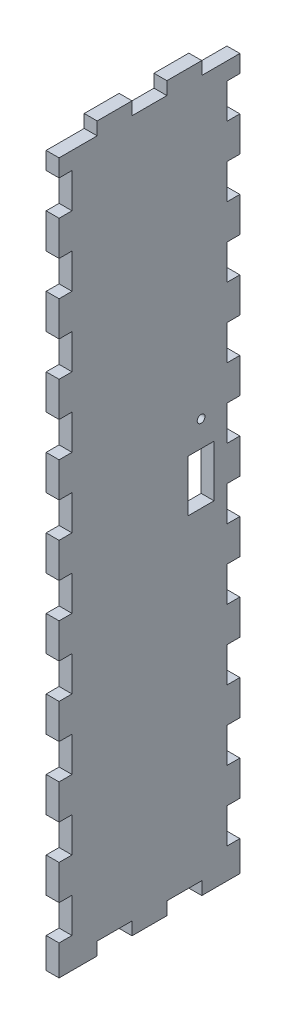
SolidWorks part; units mm, degrees
ref_plane "Front Plane" through (0, 0, 0) normal (0, 0, 1) x (1, 0, 0)
ref_plane "Top Plane" through (0, 0, 0) normal (0, 1, 0) x (1, 0, 0)
ref_plane "Right Plane" through (0, 0, 0) normal (1, 0, 0) x (0, 0, -1)
sketch "Sketch1" plane through (0, 0, 0) normal (1, 0, 0) x (0, 0, -1)
  line L0 (6.35, 355.6) -> (6.35, 349.25) construction
  line L1 (0, 0) -> (88.9, 0) construction
  line L2 (0, 0) -> (0, 6.35) construction
  line L3 (6.35, 355.6) -> (76.2, 355.6) construction
  line L4 (88.9, 0) -> (88.9, 6.35) construction
  line L5 (0, 6.35) -> (88.9, 6.35) construction
  line L6 (6.35, 349.25) -> (88.9, 349.25) construction
  line L7 (82.55, 355.6) -> (82.55, 338.1375) construction
  line L8 (0, 6.35) -> (0, 0)
  line L9 (0, 0) -> (6.35, 0)
  line L10 (6.35, 0) -> (18.7325, 0)
  line L11 (18.7325, 0) -> (18.7325, 6.35)
  line L12 (18.7325, 6.35) -> (35.8775, 6.35)
  line L13 (35.8775, 6.35) -> (35.8775, 0)
  line L14 (35.8775, 0) -> (53.0225, 0)
  line L15 (53.0225, 0) -> (53.0225, 6.35)
  line L16 (53.0225, 6.35) -> (70.1675, 6.35)
  line L17 (70.1675, 6.35) -> (70.1675, 0)
  line L18 (70.1675, 0) -> (82.55, 0)
  line L19 (82.55, 0) -> (88.9, 0)
  line L20 (88.9, 0) -> (88.9, 6.35)
  line L21 (6.35, 12.3825) -> (6.35, 0) construction
  line L22 (0, 0) -> (0, 349.25) construction
  line L23 (0, 6.35) -> (0, 14.9225)
  line L24 (0, 49.2125) -> (6.35, 49.2125)
  line L25 (6.35, 49.2125) -> (6.35, 66.3575)
  line L26 (6.35, 66.3575) -> (0, 66.3575)
  line L27 (0, 66.3575) -> (0, 83.5025)
  line L28 (0, 83.5025) -> (6.35, 83.5025)
  line L29 (6.35, 83.5025) -> (6.35, 100.6475)
  line L30 (6.35, 100.6475) -> (0, 100.6475)
  line L31 (0, 100.6475) -> (0, 117.7925)
  line L32 (0, 117.7925) -> (6.35, 117.7925)
  line L33 (6.35, 117.7925) -> (6.35, 134.9375)
  line L34 (6.35, 134.9375) -> (0, 134.9375)
  line L35 (0, 134.9375) -> (0, 152.0825)
  line L36 (0, 152.0825) -> (6.35, 152.0825)
  line L37 (6.35, 152.0825) -> (6.35, 169.2275)
  line L38 (6.35, 169.2275) -> (0, 169.2275)
  line L39 (0, 169.2275) -> (0, 186.3725)
  line L40 (0, 186.3725) -> (6.35, 186.3725)
  line L41 (6.35, 186.3725) -> (6.35, 203.5175)
  line L42 (6.35, 203.5175) -> (0, 203.5175)
  line L43 (0, 203.5175) -> (0, 220.6625)
  line L44 (0, 220.6625) -> (6.35, 220.6625)
  line L45 (6.35, 220.6625) -> (6.35, 237.8075)
  line L46 (6.35, 237.8075) -> (0, 237.8075)
  line L47 (0, 237.8075) -> (0, 254.9525)
  line L48 (0, 254.9525) -> (6.35, 254.9525)
  line L49 (6.35, 254.9525) -> (6.35, 272.0975)
  line L50 (6.35, 272.0975) -> (0, 272.0975)
  line L51 (0, 272.0975) -> (0, 289.2425)
  line L52 (0, 289.2425) -> (6.35, 289.2425)
  line L53 (6.35, 289.2425) -> (6.35, 306.3875)
  line L54 (6.35, 306.3875) -> (0, 306.3875)
  line L55 (0, 306.3875) -> (0, 323.5325)
  line L56 (0, 323.5325) -> (6.35, 323.5325)
  line L57 (6.35, 323.5325) -> (6.35, 329.692)
  line L58 (6.35, 340.6775) -> (0, 340.6775)
  line L59 (0, 340.6775) -> (0, 349.25)
  line L60 (6.35, 349.25) -> (0, 349.25)
  line L61 (6.35, 334.518) -> (6.35, 340.6775)
  line L62 (6.35, 349.25) -> (18.7325, 349.25)
  line L63 (18.7325, 349.25) -> (18.7325, 355.6)
  line L64 (18.7325, 355.6) -> (35.8775, 355.6)
  line L65 (35.8775, 355.6) -> (35.8775, 349.25)
  line L66 (35.8775, 349.25) -> (53.0225, 349.25)
  line L67 (53.0225, 349.25) -> (53.0225, 355.6)
  line L68 (53.0225, 355.6) -> (70.1675, 355.6)
  line L69 (70.1675, 355.6) -> (70.1675, 349.25)
  line L70 (70.1675, 349.25) -> (88.9, 349.25)
  line L71 (88.9, 6.35) -> (88.9, 14.9225)
  line L72 (88.9, 14.9225) -> (82.55, 14.9225)
  line L73 (82.55, 12.3825) -> (82.55, 0) construction
  line L74 (82.55, 14.9225) -> (82.55, 32.0675)
  line L75 (82.55, 32.0675) -> (88.9, 32.0675)
  line L76 (88.9, 32.0675) -> (88.9, 49.2125)
  line L77 (88.9, 66.3575) -> (88.9, 83.5025)
  line L78 (82.55, 66.3575) -> (88.9, 66.3575)
  line L79 (82.55, 49.2125) -> (82.55, 66.3575)
  line L80 (88.9, 49.2125) -> (82.55, 49.2125)
  line L81 (88.9, 100.6475) -> (88.9, 117.7925)
  line L82 (82.55, 100.6475) -> (88.9, 100.6475)
  line L83 (82.55, 83.5025) -> (82.55, 100.6475)
  line L84 (88.9, 83.5025) -> (82.55, 83.5025)
  line L85 (88.9, 134.9375) -> (88.9, 152.0825)
  line L86 (82.55, 134.9375) -> (88.9, 134.9375)
  line L87 (82.55, 117.7925) -> (82.55, 134.9375)
  line L88 (88.9, 117.7925) -> (82.55, 117.7925)
  line L89 (88.9, 169.2275) -> (88.9, 186.3725)
  line L90 (82.55, 169.2275) -> (88.9, 169.2275)
  line L91 (82.55, 152.0825) -> (82.55, 169.2275)
  line L92 (88.9, 152.0825) -> (82.55, 152.0825)
  line L93 (88.9, 203.5175) -> (88.9, 220.6625)
  line L94 (82.55, 203.5175) -> (88.9, 203.5175)
  line L95 (82.55, 186.3725) -> (82.55, 203.5175)
  line L96 (88.9, 186.3725) -> (82.55, 186.3725)
  line L97 (88.9, 237.8075) -> (88.9, 254.9525)
  line L98 (82.55, 237.8075) -> (88.9, 237.8075)
  line L99 (82.55, 220.6625) -> (82.55, 237.8075)
  line L100 (88.9, 220.6625) -> (82.55, 220.6625)
  line L101 (88.9, 272.0975) -> (88.9, 289.2425)
  line L102 (82.55, 272.0975) -> (88.9, 272.0975)
  line L103 (82.55, 254.9525) -> (82.55, 272.0975)
  line L104 (88.9, 254.9525) -> (82.55, 254.9525)
  line L105 (88.9, 306.3875) -> (88.9, 323.5325)
  line L106 (82.55, 306.3875) -> (88.9, 306.3875)
  line L107 (82.55, 289.2425) -> (82.55, 306.3875)
  line L108 (88.9, 289.2425) -> (82.55, 289.2425)
  line L109 (88.9, 340.6775) -> (88.9, 349.25)
  line L110 (82.55, 340.6775) -> (88.9, 340.6775)
  line L111 (88.9, 6.35) -> (88.9, 0)
  line L112 (82.55, 323.5325) -> (82.55, 340.6775)
  line L113 (0, 46.6725) -> (0, 49.2125) construction
  line L114 (88.9, 323.5325) -> (82.55, 323.5325)
  line L115 (0, 14.9225) -> (6.35, 14.9225)
  line L116 (6.35, 14.9225) -> (6.35, 21.082)
  line L117 (6.35, 32.0675) -> (0, 32.0675)
  line L118 (0, 32.0675) -> (0, 49.2125)
  line L119 (6.35, 334.518) -> (6.35, 329.692)
  line L120 (6.35, 25.908) -> (6.35, 21.082)
  line L127 (0, 177.8) -> (88.9237, 177.8) construction
  line L135 (6.35, 25.908) -> (6.35, 32.0675)
  line L136 (76.2, 190.5) -> (63.5, 190.5)
  line L138 (76.2, 190.5) -> (76.2, 165.1)
  line L139 (76.2, 165.1) -> (63.5, 165.1)
  line L140 (63.5, 190.5) -> (63.5, 165.1)
  circle A0 centre (69.85, 203.2) radius 1.905
  point P139 (76.2, 177.8)
  point P140 (63.5, 177.8)
  dimension "D13" = 12.7
  dimension "D14" = 6.35
  dimension "D2" = 10
  dimension "D3" = 6.35
  dimension "D4" = 6.35
  dimension "D5" = 6.35
  dimension "D6" = 6.35
  dimension "D7" = 12.3825
  dimension "D8" = 17.145
  dimension "D9" = 17.145
  dimension "D10" = 12.3825
  dimension "D11" = 8.5725
  dimension "D12" = 10
  dimension "D15" = 6.35
  dimension "D17" = 6.35
  dimension "D18" = 17.145
  dimension "D19" = 12.3825
  dimension "D20" = 17.145
  dimension "D21" = 17.145
  dimension "D22" = 17.145
  dimension "D23" = 18.7325
  dimension "D24" = 12.7
  dimension "D25" = 12.7
extrude "Boss-Extrude1" add sketch "Sketch1" along normal blind 6.35
